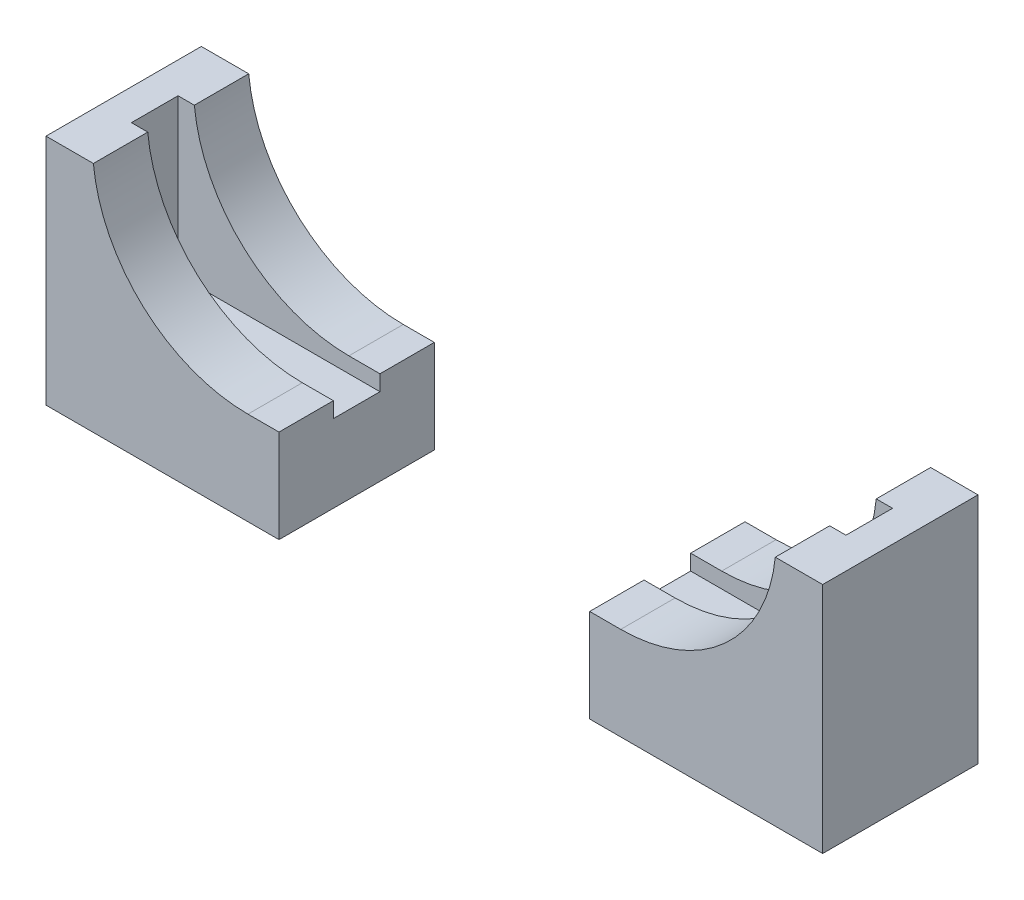
SolidWorks part; units mm, degrees
material "ABS"
ref_plane "Front" through (0, 0, 0) normal (0, 0, 1) x (1, 0, 0)
ref_plane "Top" through (0, 0, 0) normal (0, 1, 0) x (1, 0, 0)
ref_plane "Right" through (0, 0, 0) normal (1, 0, 0) x (0, 0, -1)
sketch "Sketch1" plane through (0, 0, 0) normal (0, 1, 0) x (1, 0, 0)
  line L1 (-25, -5) -> (25, -5)
  line L2 (-25, -5) -> (-25, 5)
  line L3 (-25, 5) -> (25, 5)
  line L4 (25, -5) -> (25, 5)
  line L5 (-25, -5) -> (25, 5) construction
  line L6 (-25, 5) -> (25, -5) construction
  point P0 (0, 0)
  dimension "D1" = 10
  dimension "D2" = 50
extrude "Boss-Extrude1" add sketch "Sketch1" along normal blind 15
sketch "Sketch3" plane through (0, 15, 0) normal (0, 1, 0) x (1, 0, 0)
  line L1 (-23, 1.5) -> (23, 1.5)
  line L2 (-23, 1.5) -> (-23, -1.5)
  line L3 (-23, -1.5) -> (23, -1.5)
  line L4 (23, 1.5) -> (23, -1.5)
  line L5 (-23, 1.5) -> (23, -1.5) construction
  line L6 (-23, -1.5) -> (23, 1.5) construction
  point P0 (0, 0)
  dimension "D1" = 46
  dimension "D2" = 3
extrude "Cut-Extrude1" cut sketch "Sketch3" against normal blind 10
sketch "Sketch4" plane through (0, 0, 5) normal (0, 0, 1) x (1, 0, 0)
  line L0 (0, 0) -> (-23, 0) construction
  line L1 (-25, 0) -> (25, 0) construction
  line L2 (0, 0) -> (23, 0) construction
  line L3 (-10, 0) -> (-10, 6)
  line L4 (0, 0) -> (0, 15)
  line L5 (-25, 15) -> (25, 15) construction
  line L6 (-10, 6) -> (-12, 6)
  line L7 (-22, 16) -> (-22, 15)
  line L8 (-22, 15) -> (22, 15)
  line L9 (-10, 0) -> (10, 0)
  line L10 (10, 0) -> (10, 6)
  line L11 (10, 6) -> (12, 6)
  line L12 (22, 16) -> (22, 15)
  line L13 (10, 0) -> (10, 6)
  line L14 (10, 6) -> (12, 6)
  line L15 (22, 16) -> (22, 15)
  arc A0 (-12, 6) -> (-22, 16) centre (-12, 16) cw
  arc A1 (12, 6) -> (22, 16) centre (12, 16) ccw
  point P19 (-22, 6)
  line M3 (-25, 0) -> (25, 0)
  line M5 (25, 15) -> (-25, 15)
  dimension "D5" = 10
  dimension "D1" = 23
  dimension "D2" = 23
  dimension "D3" = 6
  dimension "D4" = 10
  dimension "6" = 12
extrude "Cut-Extrude2" cut sketch "Sketch4" against normal blind 10 contours L7 L6 L3 L4 M3 M5 | L11 L12 L4 L10 M5 M3
